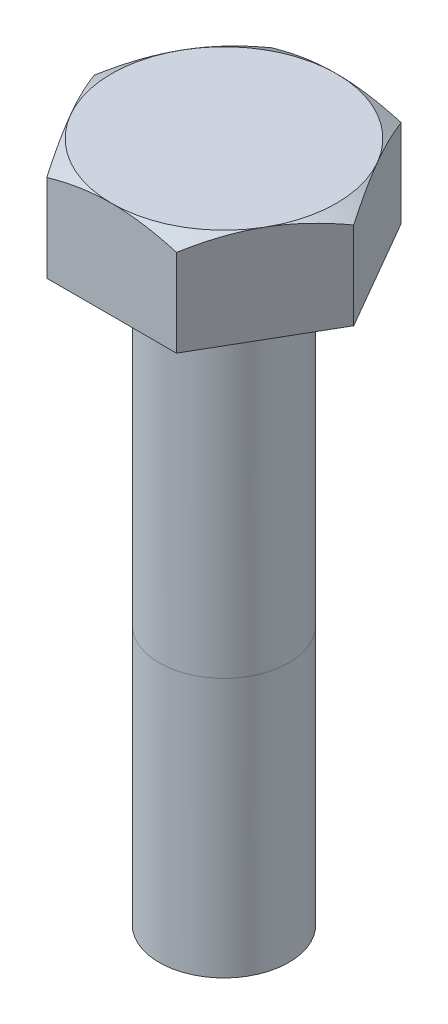
SolidWorks part; units mm, degrees
ref_plane "Front Plane" through (0, 0, 0) normal (0, 0, 1) x (1, 0, 0)
ref_plane "Top Plane" through (0, 0, 0) normal (0, 1, 0) x (1, 0, 0)
ref_plane "Right Plane" through (0, 0, 0) normal (1, 0, 0) x (0, 0, -1)
sketch "Sketch1" plane through (0, 0, 0) normal (0, 1, 0) x (1, 0, 0)
  line L1 (10, -17.3205) -> (20, 0)
  line L2 (20, 0) -> (10, 17.3205)
  line L3 (10, 17.3205) -> (-10, 17.3205)
  line L4 (-10, 17.3205) -> (-20, 0)
  line L5 (-20, 0) -> (-10, -17.3205)
  line L6 (-10, -17.3205) -> (10, -17.3205)
  circle A0 centre (0, 0) radius 17.3205 construction
  dimension "D1" = 20
extrude "Boss-Extrude1" add sketch "Sketch1" along normal blind 15
sketch "Sketch2" plane through (0, 0, 0) normal (0, -1, 0) x (1, 0, 0)
  circle A0 centre (0, 0) radius 10
  dimension "D1" = 20
extrude "Boss-Extrude2" add sketch "Sketch2" along normal blind 90 contours A0
sketch "Sketch3" plane through (0, 15, 0) normal (0, 1, 0) x (1, 0, 0)
  circle A0 centre (0, 0) radius 17.3205
extrude "Cut-Extrude2" cut sketch "Sketch3" against normal through all draft 60 flip side to cut
sketch "Sketch4" plane through (0, 0, 0) normal (1, 0, 0) x (0, 0, -1)
  line L0 (-10, -50) -> (10, -50)
  line L1 (-10, 0) -> (-10, -90) construction
  line L2 (-10, -90) -> (10, -90) construction
  line L3 (10, -90) -> (10, 0) construction
  point P6 (0, 0)
  dimension "D1" = 40
split line "Split Line5"
